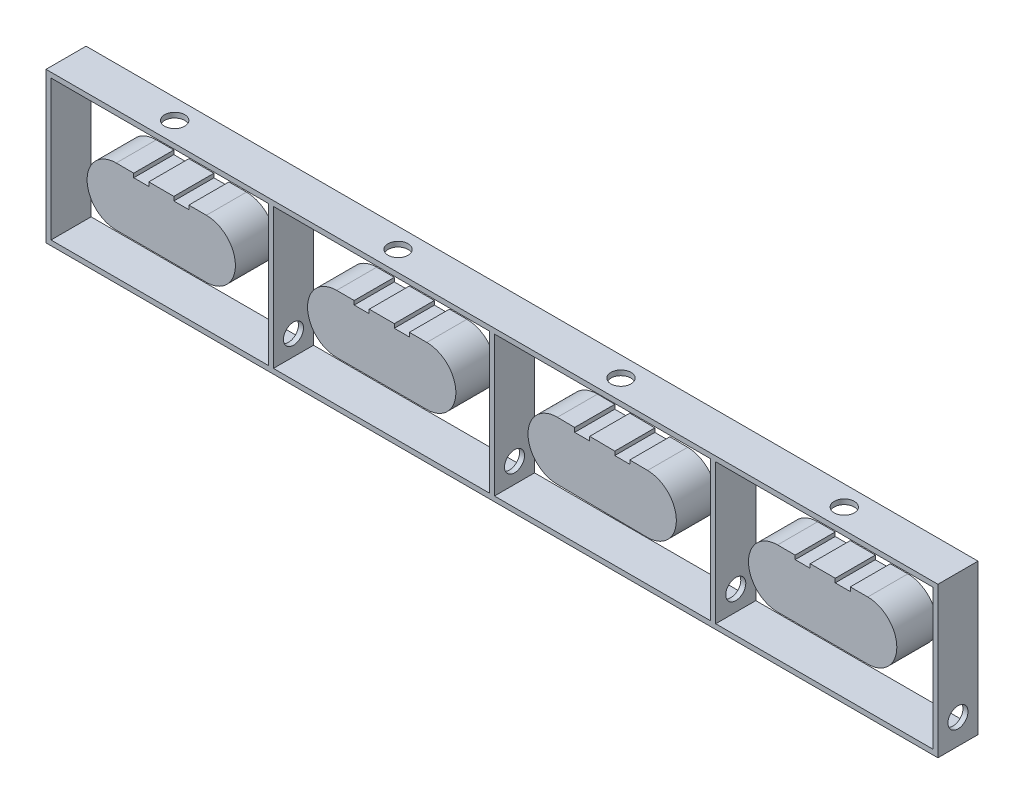
SolidWorks part; units mm, degrees
ref_plane "Front Plane" through (0, 0, 0) normal (0, 0, 1) x (1, 0, 0)
ref_plane "Top Plane" through (0, 0, 0) normal (0, 1, 0) x (1, 0, 0)
ref_plane "Right Plane" through (0, 0, 0) normal (1, 0, 0) x (0, 0, -1)
sketch "Sketch1" plane through (0, 0, 0) normal (0, 0, 1) x (1, 0, 0)
  line L12 (-890, 150) -> (890, 150)
  line L15 (-890, 150) -> (-890, -150)
  line L20 (-880, 140) -> (880, 140)
  line L21 (-880, 140) -> (-880, -140)
  line L22 (-880, -140) -> (880, -140)
  line L23 (880, 140) -> (880, -140)
  line L24 (-880, 140) -> (880, -140) construction
  line L25 (-880, -140) -> (880, 140) construction
  line L26 (-890, -150) -> (890, -150)
  line L27 (890, 150) -> (890, -150)
  line L28 (-890, 150) -> (890, -150) construction
  line L29 (-890, -150) -> (890, 150) construction
  line L30 (-440, 595.9483) -> (-440, -621.4563) construction
  line L31 (0, 595.9483) -> (0, -621.4563) construction
  line L32 (440, 595.9518) -> (440, -521.1242) construction
  line L33 (-749.9999, 0.1565) -> (-569.9999, -0.1565) construction
  line L34 (-749.899, 58.1565) -> (-569.899, 57.8434)
  line L35 (-750.1008, -57.8434) -> (-570.1008, -58.1565)
  line L39 (-310, 0) -> (-130, 0) construction
  line L40 (-310, 58) -> (-130, 58)
  line L41 (-310, -58) -> (-130, -58)
  line L42 (130.0032, 0.9431) -> (310.0032, -0.9431) construction
  line L43 (130.6109, 58.9399) -> (310.6109, 57.0537)
  line L44 (129.3954, -57.0537) -> (309.3954, -58.9399)
  line L45 (570, 0) -> (750, 0) construction
  line L46 (570, 58) -> (750, 58)
  line L47 (570, -58) -> (750, -58)
  arc A4 (-749.899, 58.1565) -> (-750.1008, -57.8434) centre (-749.9999, 0.1565) ccw
  arc A5 (-570.1008, -58.1565) -> (-569.899, 57.8434) centre (-569.9999, -0.1565) ccw
  arc A6 (-310, 58) -> (-310, -58) centre (-310, 0) ccw
  arc A7 (-130, -58) -> (-130, 58) centre (-130, 0) ccw
  arc A8 (130.6109, 58.9399) -> (129.3954, -57.0537) centre (130.0032, 0.9431) ccw
  arc A9 (309.3954, -58.9399) -> (310.6109, 57.0537) centre (310.0032, -0.9431) ccw
  arc A10 (570, 58) -> (570, -58) centre (570, 0) ccw
  arc A11 (750, -58) -> (750, 58) centre (750, 0) ccw
  point P0 (808, 0)
  point P1 (368, -1.5509)
  point P3 (0, 0)
  point P4 (0, 0)
  point P8 (0, 0)
  point P22 (440, 37.4138)
  point P25 (-659.9999, 0)
  point P38 (-220, 0)
  point P43 (-72, 0)
  point P44 (-512, -0.2574)
  point P47 (220.0032, 0)
  point P53 (660, 0)
  dimension "D12" = 140
  dimension "D11" = 58
  dimension "D15" = 58
  dimension "D20" = 58
  dimension "D21" = 58
  dimension "D24" = 140
  dimension "D1" = 10
  dimension "D2" = 10
  dimension "D3" = 140
  dimension "D4" = 1780
  dimension "D5" = 440
  dimension "D6" = 440
  dimension "D7" = 440
  dimension "D8" = 440
  dimension "D9" = 140
  dimension "D10" = 180
  dimension "D13" = 140
  dimension "D14" = 72
  dimension "D16" = 180
  dimension "D17" = 72
  dimension "D18" = 72
  dimension "D19" = 180
  dimension "D22" = 180
  dimension "D23" = 72
  dimension "D25" = 140
  dimension "D26" = 140
  dimension "D27" = 140
extrude "Boss-Extrude1" add sketch "Sketch1" along normal mid plane 80 contours L27 L12 L15 L26 L20 L23 L22 L21 | L35 A5 L34 A4 | L41 A7 L40 A6 | L44 A9 L43 A8 | L47 A11 L46 A10
sketch "Sketch2" plane through (0, 0, 40) normal (0, 0, 1) x (1, 0, 0)
  line L0 (-807.9998, 0.2574) -> (49192.0002, 0.2574) construction
  line L1 (-659.899, 57.987) -> (-659.899, -49942.013) construction
  line L2 (-749.899, 58.1565) -> (-569.899, 57.8434) construction
  line L3 (-274.899, 61.1691) -> (-274.899, 50.0956)
  line L4 (-714.899, 61.1691) -> (-684.899, 61.1691)
  line L5 (-714.899, 61.1691) -> (-714.899, 50.0956)
  line L6 (-714.899, 50.0956) -> (-684.899, 50.0956)
  line L7 (-684.899, 61.1691) -> (-684.899, 50.0956)
  line L8 (-634.899, 59.4459) -> (-604.899, 59.4459)
  line L9 (-634.899, 59.4459) -> (-634.899, 49.9564)
  line L10 (-634.899, 49.9564) -> (-604.899, 49.9564)
  line L11 (-604.899, 59.4459) -> (-604.899, 49.9564)
  line L12 (-274.899, 61.1691) -> (-244.899, 61.1691)
  line L13 (-244.899, 61.1691) -> (-244.899, 50.0956)
  line L14 (-274.899, 50.0956) -> (-244.899, 50.0956)
  line L15 (-194.899, 59.4459) -> (-194.899, 49.9564)
  line L16 (-194.899, 59.4459) -> (-164.899, 59.4459)
  line L17 (-164.899, 59.4459) -> (-164.899, 49.9564)
  line L18 (-194.899, 49.9564) -> (-164.899, 49.9564)
  line L19 (165.101, 61.1691) -> (165.101, 50.0956)
  line L20 (165.101, 61.1691) -> (195.101, 61.1691)
  line L21 (195.101, 61.1691) -> (195.101, 50.0956)
  line L22 (165.101, 50.0956) -> (195.101, 50.0956)
  line L23 (245.101, 59.4459) -> (245.101, 49.9564)
  line L24 (245.101, 59.4459) -> (275.101, 59.4459)
  line L25 (275.101, 59.4459) -> (275.101, 49.9564)
  line L26 (245.101, 49.9564) -> (275.101, 49.9564)
  line L27 (605.101, 61.1691) -> (605.101, 50.0956)
  line L28 (605.101, 61.1691) -> (635.101, 61.1691)
  line L29 (635.101, 61.1691) -> (635.101, 50.0956)
  line L30 (605.101, 50.0956) -> (635.101, 50.0956)
  line L31 (685.101, 59.4459) -> (685.101, 49.9564)
  line L32 (685.101, 59.4459) -> (715.101, 59.4459)
  line L33 (715.101, 59.4459) -> (715.101, 49.9564)
  line L34 (685.101, 49.9564) -> (715.101, 49.9564)
  line L36 (-220, 58) -> (-220, 19.35) construction
  line L37 (-310, 58) -> (-130, 58) construction
  arc A0 (-749.899, 58.1565) -> (-750.1008, -57.8434) centre (-749.9999, 0.1565) ccw construction
  point P5 (-807.9998, 0.2574)
  point P10 (-659.899, 57.9999)
  line M4 (-569.899, 57.8434) -> (-749.899, 58.1565)
  dimension "D3" = 30
  dimension "D4" = 30
  dimension "D5" = 25
  dimension "D6" = 25
  dimension "D7" = 4
extrude "Cut-Extrude1" cut sketch "Sketch2" against normal through all both and the other way through all contours L7 L5 L6 M4 | L11 L9 L10 M4 | L15 L18 L17 L16 | L3 L14 L13 L12 | L19 L22 L21 L20 | L23 L26 L25 L24 | L31 L34 L33 L32 | L27 L30 L29 L28
sketch "Sketch3" plane through (0, 150, 0) normal (0, 1, 0) x (1, 0, 0)
  line L0 (-441.1466, -40) -> (-441.1466, 40)
  line L1 (-890, -40) -> (890, -40) construction
  line L2 (-890, 40) -> (890, 40) construction
  line L3 (0, -40) -> (0, 40)
  line L4 (441.5653, -40) -> (441.5653, 40)
extrude "Extrude-Thin1" add sketch "Sketch3" against normal up to surface (280 mm away) from surface at -10 thin up to face at (0, -140, 0) starting at face at (0, 140, 0) thin type mid plane wall 10
sketch "Sketch4" plane through (0, 150, 0) normal (0, 1, 0) x (1, 0, 0)
  line L0 (-890, 40) -> (890, 40) construction
  circle A0 centre (663.1028, 0) radius 20
  circle A1 centre (217.4618, 0) radius 20
  circle A2 centre (-227.3076, 0) radius 20
  circle A3 centre (-673.2117, 0) radius 20
  dimension "D2" = 40
  dimension "D1" = 40
extrude "Cut-Extrude2" cut sketch "Sketch4" against normal blind 47
sketch "Sketch6" plane through (890, 0, 0) normal (1, 0, 0) x (0, 0, -1)
  line L0 (-40, 150) -> (-40, -150) construction
  circle A0 centre (0, -100) radius 20
  dimension "D1" = 40
  dimension "D2" = 100
  dimension "D3" = 40
extrude "Cut-Extrude4" cut sketch "Sketch6" against normal blind 1437
